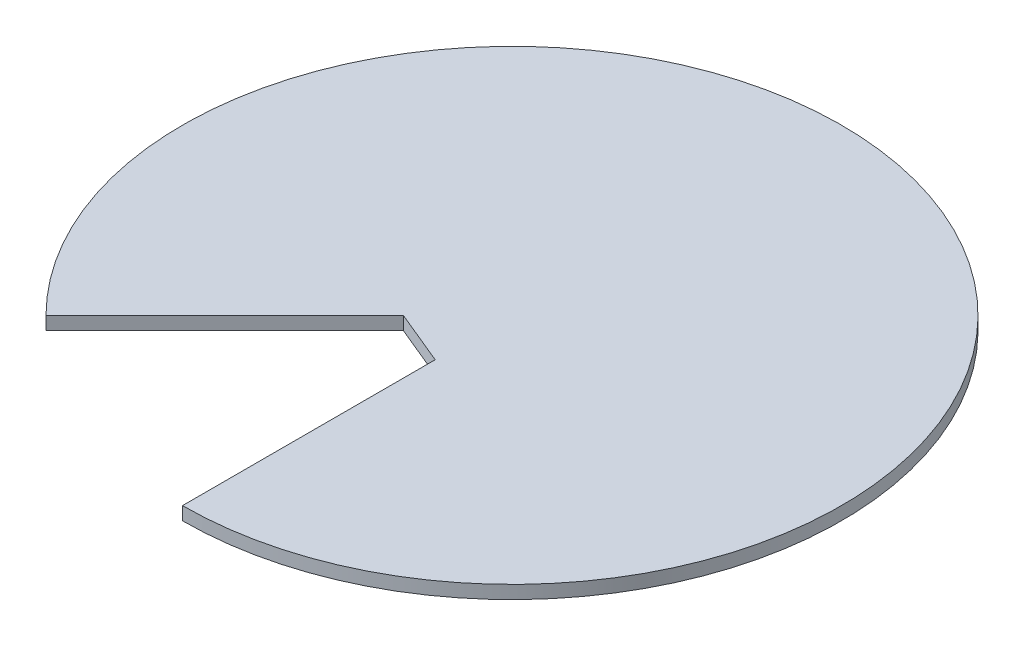
SolidWorks part; units mm, degrees
ref_plane "Front Plane" through (0, 0, 0) normal (0, 0, 1) x (1, 0, 0)
ref_plane "Top Plane" through (0, 0, 0) normal (0, 1, 0) x (1, 0, 0)
ref_plane "Right Plane" through (0, 0, 0) normal (1, 0, 0) x (0, 0, -1)
sketch "Sketch1" plane through (0, 0, 0) normal (0, 1, 0) x (1, 0, 0)
  line L0 (65.1247, -37.1991) -> (72.3539, 19.7464) construction
  line L1 (37.1991, 65.1247) -> (-19.7464, 72.3539) construction
  line L2 (-19.7464, 72.3539) -> (-65.1247, 37.1991) construction
  line L3 (-65.1247, 37.1991) -> (-72.3539, -19.7464) construction
  line L4 (-72.3539, -19.7464) -> (-37.1991, -65.1247) construction
  line L5 (-37.1991, -65.1247) -> (19.7464, -72.3539) construction
  line L6 (19.7464, -72.3539) -> (65.1247, -37.1991) construction
  line L7 (72.3539, 19.7464) -> (37.1991, 65.1247) construction
  line L8 (-37.1991, -65.1247) -> (0, 0)
  line L9 (0, 0) -> (19.7464, -72.3539)
  circle A0 centre (0, 0) radius 75
  circle A1 centre (0, 0) radius 75 construction
  arc A2 (19.7464, -72.3539) -> (-37.1991, -65.1247) centre (0, 0) cw
extrude "Boss-Extrude1" add sketch "Sketch1" along normal blind 3 contours A0
sketch "Sketch2" plane through (0, 3, 0) normal (0, 1, 0) x (1, 0, 0)
  line L0 (-53.033, -53.033) -> (0, 0) construction
  line L1 (0, 75) -> (-53.033, 53.033) construction
  line L2 (-53.033, 53.033) -> (-75, 0) construction
  line L3 (-75, 0) -> (-53.033, -53.033) construction
  line L4 (-53.033, -53.033) -> (0, -75) construction
  line L5 (0, -75) -> (53.033, -53.033) construction
  line L6 (53.033, -53.033) -> (75, 0) construction
  line L7 (75, 0) -> (53.033, 53.033) construction
  line L8 (53.033, 53.033) -> (0, 75) construction
  line L9 (0, 0) -> (0, -75) construction
  line L10 (-53.033, -53.033) -> (-12.3663, -12.3663)
  line L11 (-12.3663, -12.3663) -> (0, -17.4886)
  line L12 (0, -17.4886) -> (0, -75)
  circle A0 centre (0, 0) radius 75 construction
  arc A1 (0, -75) -> (-53.033, -53.033) centre (0, 0) cw
  point P14 (0, 0)
extrude "Cut-Extrude1" cut sketch "Sketch2" against normal blind 3
